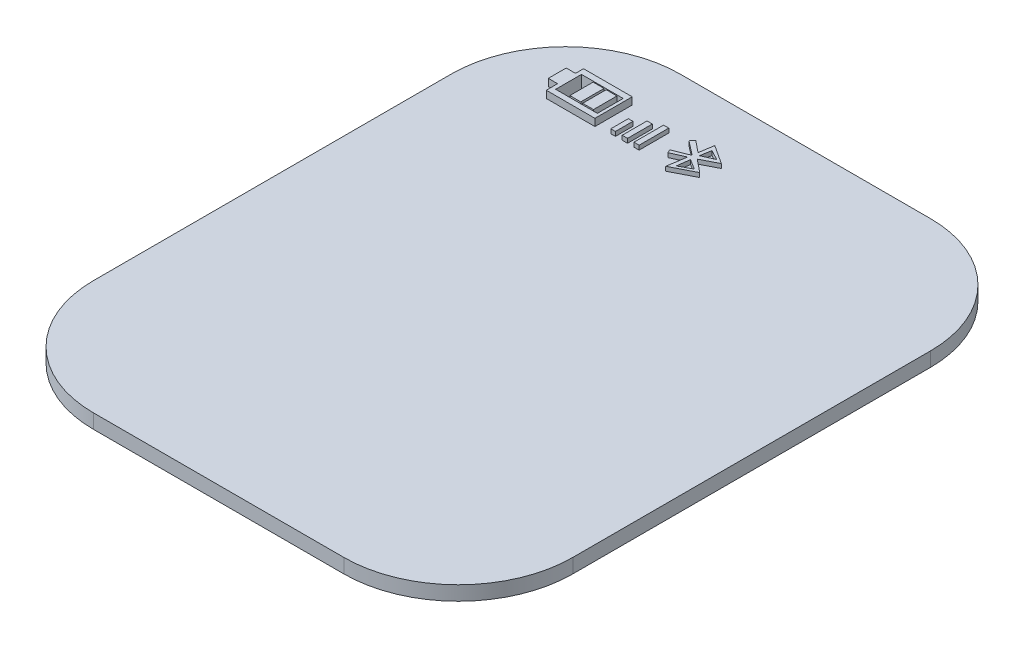
SolidWorks part; units mm, degrees
ref_plane "Front Plane" through (0, 0, 0) normal (0, 0, 1) x (1, 0, 0)
ref_plane "Top Plane" through (0, 0, 0) normal (0, 1, 0) x (1, 0, 0)
ref_plane "Right Plane" through (0, 0, 0) normal (1, 0, 0) x (0, 0, -1)
sketch "Sketch1" plane through (0, 0, 0) normal (0, 1, 0) x (1, 0, 0)
  line L1 (-8.75, 20.5) -> (8.75, 20.5)
  line L2 (-16.75, 12.5) -> (-16.75, -12.5)
  line L3 (-8.75, -20.5) -> (8.75, -20.5)
  line L4 (16.75, 12.5) -> (16.75, -12.5)
  line L5 (-16.75, 20.5) -> (16.75, -20.5) construction
  line L6 (-16.75, -20.5) -> (16.75, 20.5) construction
  arc A0 (-16.75, -12.5) -> (-8.75, -20.5) centre (-8.75, -12.5) ccw
  arc A1 (8.75, 20.5) -> (16.75, 12.5) centre (8.75, 12.5) cw
  arc A2 (-8.75, 20.5) -> (-16.75, 12.5) centre (-8.75, 12.5) ccw
  arc A3 (8.75, -20.5) -> (16.75, -12.5) centre (8.75, -12.5) ccw
  point P0 (0, 0)
  dimension "D3" = 8
  dimension "D1" = 33.5
  dimension "D2" = 41
extrude "Boss-Extrude1" add sketch "Sketch1" along normal blind 1
sketch "Sketch2" plane through (0, 1, 0) normal (0, 1, 0) x (1, 0, 0)
  line L0 (-11.9506, 16.388) -> (-12.5986, 16.388)
  line L1 (-11.9506, 16.9496) -> (-8.5511, 16.9496)
  line L2 (-11.9506, 16.9496) -> (-11.9506, 14.3454)
  line L3 (-11.9506, 14.3454) -> (-8.5511, 14.3454)
  line L4 (-8.5511, 16.9496) -> (-8.5511, 14.3454)
  line L5 (-12.5986, 16.388) -> (-12.5986, 15.136)
  line L6 (-12.5986, 15.136) -> (-11.9506, 15.136)
  text T0 "150.00"
  text T1 "JK"
  point P2 (-10.2508, 15.6475)
extrude "Boss-Extrude2" add sketch "Sketch2" along normal blind 0.5 contours L4 L1 L2 L3 | L5 L6 L2 L0
sketch "Sketch3" plane through (0, 1.5, 0) normal (0, 1, 0) x (1, 0, 0)
  line L1 (-11.6788, 16.5336) -> (-8.7649, 16.5336)
  line L2 (-11.6788, 16.5336) -> (-11.6788, 14.7306)
  line L3 (-11.6788, 14.7306) -> (-8.7649, 14.7306)
  line L4 (-8.7649, 16.5336) -> (-8.7649, 14.7306)
  line L5 (-11.6788, 16.5336) -> (-8.7649, 14.7306) construction
  line L6 (-11.6788, 14.7306) -> (-8.7649, 16.5336) construction
  point P0 (-10.2218, 15.6321)
  point P5 (-10.5268, 15.7763)
  point P6 (-11.6788, 14.6152)
extrude "Cut-Extrude1" cut sketch "Sketch3" against normal blind 1
sketch "Sketch4" plane through (0, 0.5, 0) normal (0, 1, 0) x (1, 0, 0)
  line L1 (-9.8877, 16.4665) -> (-9.1324, 16.4665)
  line L2 (-9.8877, 16.4665) -> (-9.8877, 14.8266)
  line L3 (-9.8877, 14.8266) -> (-9.1324, 14.8266)
  line L4 (-9.1324, 16.4665) -> (-9.1324, 14.8266)
  line L5 (-9.8877, 16.4665) -> (-9.1324, 14.8266) construction
  line L6 (-9.8877, 14.8266) -> (-9.1324, 16.4665) construction
  line L7 (-10.8033, 16.4717) -> (-10.0396, 16.4717)
  line L8 (-10.8033, 16.4717) -> (-10.8033, 14.8456)
  line L9 (-10.8033, 14.8456) -> (-10.0396, 14.8456)
  line L10 (-10.0396, 16.4717) -> (-10.0396, 14.8456)
  line L11 (-10.8033, 16.4717) -> (-10.0396, 14.8456) construction
  line L12 (-10.8033, 14.8456) -> (-10.0396, 16.4717) construction
  point P0 (-9.5101, 15.6465)
  point P6 (-10.4215, 15.6587)
extrude "Boss-Extrude3" add sketch "Sketch4" along normal blind 1
sketch "Sketch5" plane through (0, 1, 0) normal (0, 1, 0) x (1, 0, 0)
  text T0 "70 mg/dl"
  text T1 "BLOOD"
  text T2 "Glucose"
sketch "Sketch6" plane through (0, 1, 0) normal (0, 1, 0) x (1, 0, 0)
  line L1 (-7.563, 14.4671) -> (-7.24, 14.4671)
  line L2 (-7.563, 14.4671) -> (-7.563, 15.692)
  line L3 (-7.563, 15.692) -> (-7.24, 15.692)
  line L4 (-7.24, 14.4671) -> (-7.24, 15.692)
  line L5 (-7.563, 14.4671) -> (-7.24, 15.692) construction
  line L6 (-7.563, 15.692) -> (-7.24, 14.4671) construction
  line L7 (-6.7715, 14.4731) -> (-6.3997, 14.4731)
  line L8 (-6.7715, 14.4731) -> (-6.7715, 16.2082)
  line L9 (-6.7715, 16.2082) -> (-6.3997, 16.2082)
  line L10 (-6.3997, 14.4731) -> (-6.3997, 16.2082)
  line L11 (-6.7715, 14.4731) -> (-6.3997, 16.2082) construction
  line L12 (-6.7715, 16.2082) -> (-6.3997, 14.4731) construction
  line L13 (-5.9406, 16.5339) -> (-5.5791, 16.5339)
  line L14 (-5.9406, 16.5339) -> (-5.9406, 14.4631)
  line L15 (-5.9406, 14.4631) -> (-5.5791, 14.4631)
  line L16 (-5.5791, 16.5339) -> (-5.5791, 14.4631)
  line L17 (-5.9406, 16.5339) -> (-5.5791, 14.4631) construction
  line L18 (-5.9406, 14.4631) -> (-5.5791, 16.5339) construction
  point P0 (-7.4015, 15.0795)
  point P5 (-5.7598, 15.4985)
  point P6 (-6.5856, 15.3406)
  point P11 (-5.7598, 15.4985)
extrude "Boss-Extrude4" add sketch "Sketch6" along normal blind 0.3
sketch "Sketch7" plane through (0, 1, 0) normal (0, 1, 0) x (1, 0, 0)
  line L0 (-2.9133, 17.0833) -> (-3.0708, 16.0694)
  line L1 (-3.3741, 14.1168) -> (-1.8015, 14.9211)
  line L2 (-1.8015, 14.9211) -> (-2.7076, 15.6531)
  line L3 (-2.7076, 15.6531) -> (-1.5944, 16.2225)
  line L4 (-1.5944, 16.2225) -> (-2.9133, 17.0833)
  line L5 (-3.1288, 15.6961) -> (-4.2207, 15.2519)
  line L6 (-4.2207, 15.2519) -> (-4.1259, 15.019)
  line L7 (-4.1259, 15.019) -> (-3.1689, 15.438)
  line L8 (-3.0708, 16.0694) -> (-3.89, 16.7348)
  line L9 (-3.89, 16.7348) -> (-4.1046, 16.4705)
  line L10 (-4.1046, 16.4705) -> (-3.1258, 15.7155)
  line L11 (-2.9133, 15.3899) -> (-3.0251, 14.5025)
  line L12 (-3.0251, 14.5025) -> (-2.2087, 14.9462)
  line L13 (-2.2087, 14.9462) -> (-2.9133, 15.3899)
  line L14 (-2.8347, 15.9352) -> (-2.7076, 16.6782)
  line L15 (-2.7076, 16.6782) -> (-1.9939, 16.3067)
  line L16 (-1.9939, 16.3067) -> (-2.8347, 15.9352)
  line L17 (-3.1689, 15.438) -> (-3.3741, 14.1168)
  line L18 (-3.1258, 15.7155) -> (-3.1288, 15.6961)
  point P19 (-2.9103, 15.3899)
extrude "Boss-Extrude8" add sketch "Sketch7" along normal blind 0.3
